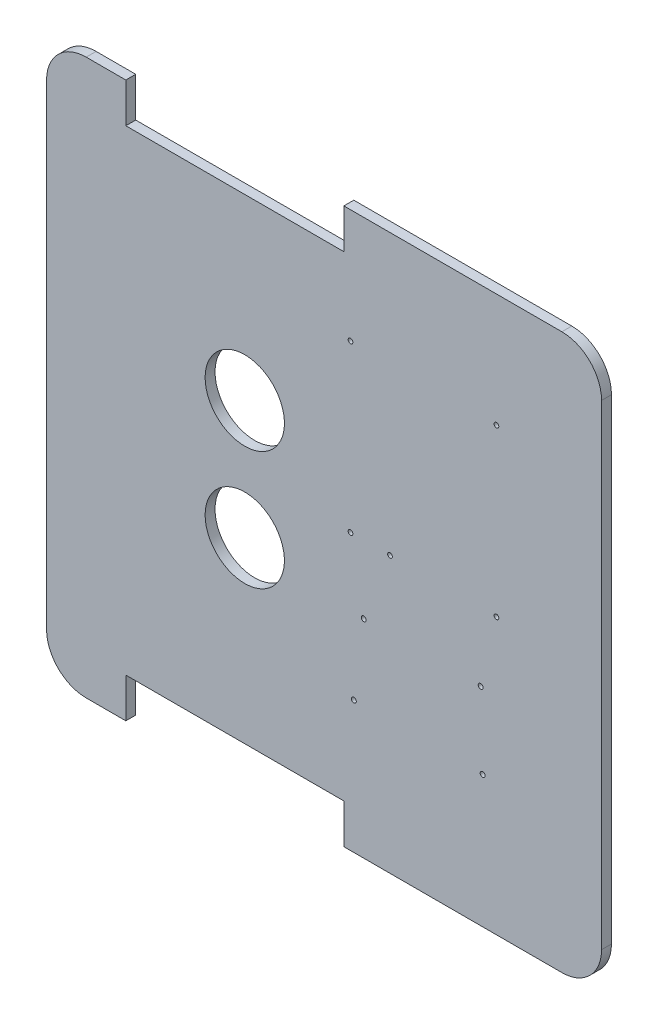
SolidWorks part; units mm, degrees
ref_plane "Front Plane" through (0, 0, 0) normal (0, 0, 1) x (1, 0, 0)
ref_plane "Top Plane" through (0, 0, 0) normal (0, 1, 0) x (1, 0, 0)
ref_plane "Right Plane" through (0, 0, 0) normal (1, 0, 0) x (0, 0, -1)
sketch "Sketch1" plane through (0, 0, 0) normal (0, 0, 1) x (1, 0, 0)
  line L1 (25.4, 0) -> (330.2, 0)
  line L2 (0, 25.4) -> (0, 330.2)
  line L3 (25.4, 355.6) -> (330.2, 355.6)
  line L4 (355.6, 25.4) -> (355.6, 330.2)
  arc A0 (25.4, 0) -> (0, 25.4) centre (25.4, 25.4) cw
  arc A1 (330.2, 0) -> (355.6, 25.4) centre (330.2, 25.4) ccw
  arc A2 (330.2, 355.6) -> (355.6, 330.2) centre (330.2, 330.2) cw
  arc A3 (0, 330.2) -> (25.4, 355.6) centre (25.4, 330.2) cw
  point P7 (0, 0)
  point P10 (355.6, 0)
  point P15 (0, 355.6)
  dimension "D3" = 25.4
  dimension "D1" = 355.6
  dimension "D2" = 355.6
extrude "Boss-Extrude1" add sketch "Sketch1" along normal blind 6.35
sketch "Sketch2" plane through (0, 0, 0) normal (0, 0, -1) x (-1, 0, 0)
  line L0 (-330.2, 355.6) -> (-25.4, 355.6) construction
  line L1 (-190.5, 355.6) -> (-50.8, 355.6)
  line L2 (-190.5, 355.6) -> (-190.5, 330.2)
  line L3 (-190.5, 330.2) -> (-50.8, 330.2)
  line L4 (-50.8, 355.6) -> (-50.8, 330.2)
  line L5 (-190.5, 25.4) -> (-50.8, 25.4)
  line L6 (-190.5, 25.4) -> (-190.5, 0)
  line L7 (-190.5, 0) -> (-50.8, 0)
  line L8 (-50.8, 25.4) -> (-50.8, 0)
  line L9 (-25.4, 0) -> (-330.2, 0) construction
  line L11 (0, 330.2) -> (0, 25.4) construction
  dimension "D1" = 25.4
  dimension "D2" = 25.4
  dimension "D3" = 139.7
  dimension "D4" = 50.8
extrude "Cut-Extrude1" cut sketch "Sketch2" against normal through all
sketch "Sketch4" plane through (0, 0, 0) normal (0, 0, -1) x (-1, 0, 0)
  line L12 (-190.5, 0) -> (-190.5, 25.4)
  line L13 (-190.5, 25.4) -> (-50.8, 25.4)
  line L14 (-50.8, 25.4) -> (-50.8, 0)
  line L15 (-50.8, 0) -> (-25.4, 0)
  line L16 (0, 25.4) -> (0, 330.2)
  line L17 (-25.4, 355.6) -> (-50.8, 355.6)
  line L18 (-50.8, 355.6) -> (-50.8, 330.2)
  line L19 (-50.8, 330.2) -> (-190.5, 330.2)
  line L20 (-190.5, 330.2) -> (-190.5, 355.6)
  line L21 (-190.5, 355.6) -> (-330.2, 355.6)
  line L22 (-355.6, 330.2) -> (-355.6, 25.4)
  line L23 (-330.2, 0) -> (-190.5, 0)
  line L24 (-190.5, 0) -> (-190.5, 25.4)
  line L25 (-190.5, 25.4) -> (-50.8, 25.4)
  line L26 (-50.8, 25.4) -> (-50.8, 0)
  line L27 (-50.8, 0) -> (-25.4, 0)
  line L28 (0, 25.4) -> (0, 330.2)
  line L29 (-25.4, 355.6) -> (-50.8, 355.6)
  line L30 (-50.8, 355.6) -> (-50.8, 330.2)
  line L31 (-50.8, 330.2) -> (-190.5, 330.2)
  line L32 (-190.5, 330.2) -> (-190.5, 355.6)
  line L33 (-190.5, 355.6) -> (-330.2, 355.6)
  line L34 (-355.6, 330.2) -> (-355.6, 25.4)
  line L35 (-330.2, 0) -> (-190.5, 0)
  line L36 (-355.6, 330.2) -> (-355.6, 25.4)
  line L37 (-330.2, 0) -> (-190.5, 0)
  line L38 (-190.5, 0) -> (-190.5, 25.4)
  line L39 (-190.5, 25.4) -> (-50.8, 25.4)
  line L40 (-50.8, 25.4) -> (-50.8, 0)
  line L41 (-50.8, 0) -> (-25.4, 0)
  line L42 (0, 25.4) -> (0, 330.2)
  line L43 (-25.4, 355.6) -> (-50.8, 355.6)
  line L44 (-50.8, 355.6) -> (-50.8, 330.2)
  line L45 (-50.8, 330.2) -> (-190.5, 330.2)
  line L46 (-190.5, 330.2) -> (-190.5, 355.6)
  line L47 (-190.5, 355.6) -> (-330.2, 355.6)
  line L48 (-355.6, 330.2) -> (-355.6, 25.4)
  line L49 (-330.2, 0) -> (-190.5, 0)
  line L50 (-190.5, 0) -> (-190.5, 25.4)
  line L51 (-190.5, 25.4) -> (-50.8, 25.4)
  line L52 (-50.8, 25.4) -> (-50.8, 0)
  line L53 (-50.8, 0) -> (-25.4, 0)
  line L54 (0, 25.4) -> (0, 330.2)
  line L55 (-25.4, 355.6) -> (-50.8, 355.6)
  line L56 (-50.8, 355.6) -> (-50.8, 330.2)
  line L57 (-50.8, 330.2) -> (-190.5, 330.2)
  line L58 (-190.5, 330.2) -> (-190.5, 355.6)
  line L59 (-190.5, 355.6) -> (-330.2, 355.6)
  circle A1 centre (-194.7588, 282.7721) radius 1.5
  circle A2 centre (-194.7588, 282.7721) radius 1.5
  circle A3 centre (-288.2588, 282.7721) radius 1.5
  arc A4 (-25.4, 0) -> (0, 25.4) centre (-25.4, 25.4) ccw
  arc A5 (0, 330.2) -> (-25.4, 355.6) centre (-25.4, 330.2) ccw
  arc A6 (-330.2, 355.6) -> (-355.6, 330.2) centre (-330.2, 330.2) ccw
  arc A7 (-355.6, 25.4) -> (-330.2, 0) centre (-330.2, 25.4) ccw
  arc A8 (-25.4, 0) -> (0, 25.4) centre (-25.4, 25.4) ccw
  arc A9 (0, 330.2) -> (-25.4, 355.6) centre (-25.4, 330.2) ccw
  arc A10 (-330.2, 355.6) -> (-355.6, 330.2) centre (-330.2, 330.2) ccw
  arc A11 (-355.6, 25.4) -> (-330.2, 0) centre (-330.2, 25.4) ccw
  circle A12 centre (-288.2588, 282.7721) radius 1.5
  circle A13 centre (-196.8732, 84.5738) radius 1.5875
  circle A14 centre (-196.8732, 84.5738) radius 1.5875
  circle A15 centre (-203.2232, 132.8338) radius 1.5875
  arc A16 (-355.6, 25.4) -> (-330.2, 0) centre (-330.2, 25.4) ccw
  arc A17 (-25.4, 0) -> (0, 25.4) centre (-25.4, 25.4) ccw
  arc A18 (0, 330.2) -> (-25.4, 355.6) centre (-25.4, 330.2) ccw
  arc A19 (-330.2, 355.6) -> (-355.6, 330.2) centre (-330.2, 330.2) ccw
  arc A20 (-355.6, 25.4) -> (-330.2, 0) centre (-330.2, 25.4) ccw
  arc A21 (-25.4, 0) -> (0, 25.4) centre (-25.4, 25.4) ccw
  arc A22 (0, 330.2) -> (-25.4, 355.6) centre (-25.4, 330.2) ccw
  arc A23 (-330.2, 355.6) -> (-355.6, 330.2) centre (-330.2, 330.2) ccw
  circle A24 centre (-203.2232, 132.8338) radius 1.5875
  circle A25 centre (-278.1532, 132.8338) radius 1.5875
  circle A26 centre (-278.1532, 132.8338) radius 1.5875
  circle A27 centre (-279.4232, 84.5738) radius 1.5875
  circle A28 centre (-279.4232, 84.5738) radius 1.5875
  circle A29 centre (-194.7588, 176.4721) radius 1.5
  circle A30 centre (-194.7588, 176.4721) radius 1.5
  circle A31 centre (-220.0588, 176.4721) radius 1.5
  circle A32 centre (-220.0588, 176.4721) radius 1.5
  circle A33 centre (-288.2588, 176.4721) radius 1.5
  circle A34 centre (-288.2588, 176.4721) radius 1.5
  circle A35 centre (-127, 139.7) radius 25.4
  circle A36 centre (-127, 139.7) radius 25.4
  circle A37 centre (-127, 215.9) radius 25.4
  circle A38 centre (-127, 215.9) radius 25.4
  dimension "D1" = 0
  dimension "D2" = 0
  dimension "D3" = 0
  dimension "D4" = 0
  dimension "D5" = 0
  dimension "D6" = 0
  dimension "D7" = 0
  dimension "D8" = 0
  dimension "D9" = 0
  dimension "D10" = 0
  dimension "D11" = 0
  dimension "D12" = 0
  dimension "D13" = 0
extrude "Cut-Extrude2" cut sketch "Sketch4" against normal through all contours A28 | A26 | A14 | A24 | A34 | A32 | A30 | A12 | A2 | A38 | A36
